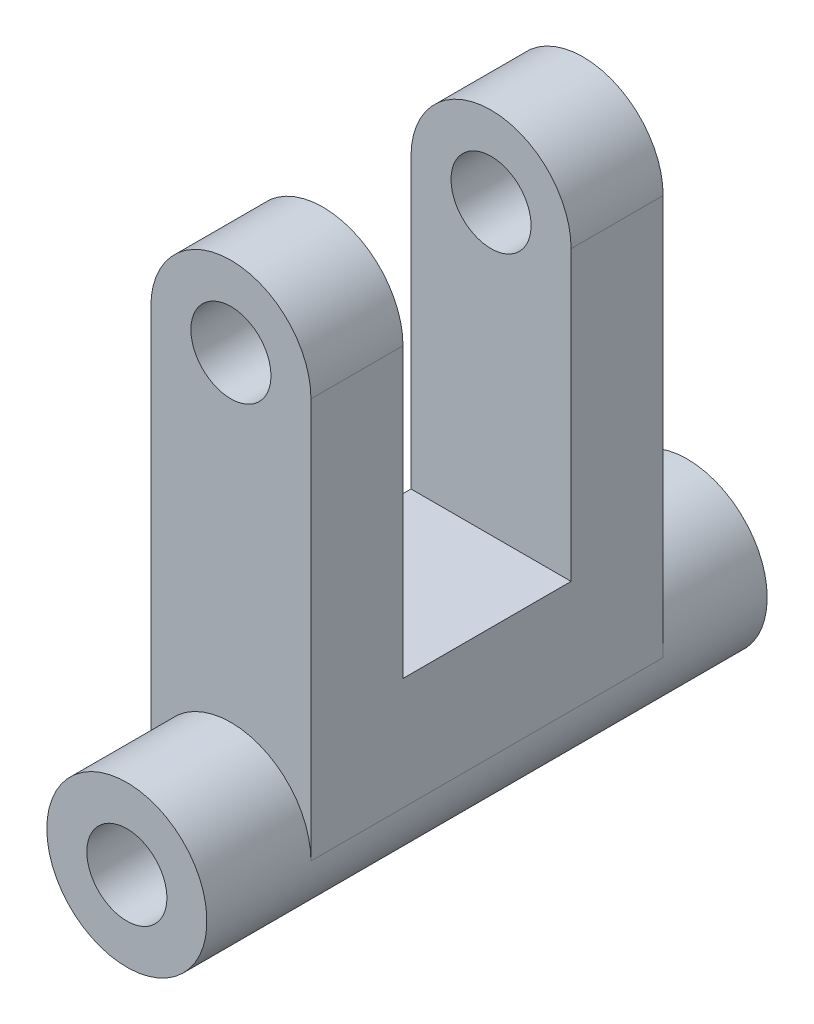
SolidWorks part; units mm, degrees
ref_plane "Front Plane" through (0, 0, 0) normal (0, 0, 1) x (1, 0, 0)
ref_plane "Top Plane" through (0, 0, 0) normal (0, 1, 0) x (1, 0, 0)
ref_plane "Right Plane" through (0, 0, 0) normal (1, 0, 0) x (0, 0, -1)
sketch "Sketch1" plane through (0, 0, 0) normal (0, 0, 1) x (1, 0, 0)
  line L0 (0, 0) -> (0, 25) construction
  line L1 (5, 25) -> (5, 0)
  line L2 (-5, 25) -> (-5, 0)
  circle A0 centre (0, 0) radius 5
  circle A1 centre (0, 0) radius 2.5
  circle A2 centre (0, 25) radius 5
  circle A3 centre (0, 25) radius 2.5
  dimension "D1" = 5
  dimension "D2" = 10
  dimension "D4" = 5
  dimension "D5" = 10
  dimension "D3" = 25
extrude "Boss-Extrude1" add sketch "Sketch1" along normal blind 5.75
sketch "Sketch2" plane through (0, 0, 5.75) normal (0, 0, 1) x (1, 0, 0)
  circle A0 centre (0, 25.0086) radius 2.5
  dimension "D1" = 5
extrude "Boss-Extrude2" add sketch "Sketch2" along normal blind 10.5 contours A0
sketch "Sketch3" plane through (0, 0, 5.75) normal (0, 0, 1) x (1, 0, 0)
  line L2 (5, 0) -> (5, 25)
  line L4 (-5, 0) -> (-5, 25)
  arc A0 (5, 25) -> (-5, 25) centre (0, 25) ccw
  arc A1 (-5, 0) -> (5, 0) centre (0, 0) ccw
extrude "Boss-Extrude3" add sketch "Sketch3" along normal blind 16.25
sketch "Sketch4" plane through (0, 0, 22) normal (0, 0, 1) x (1, 0, 0)
  circle A0 centre (0, 0) radius 5
  circle A1 centre (0, 0) radius 2.5
  dimension "D1" = 5
  dimension "D2" = 10
extrude "Boss-Extrude5" add sketch "Sketch4" along normal blind 8.5 contours A1 | A0
sketch "Sketch5" plane through (0, 0, 22) normal (0, 0, 1) x (1, 0, 0)
  circle A0 centre (0, 0) radius 2.5
extrude "Boss-Extrude6" add sketch "Sketch5" along normal blind 16.25
sketch "Sketch6" plane through (0, 0, 0) normal (0, 0, -1) x (-1, 0, 0)
  circle A0 centre (0, 0) radius 5
extrude "Boss-Extrude7" add sketch "Sketch6" along normal blind 8.5
sketch "Sketch7" plane through (0, 0, -8.5) normal (0, 0, -1) x (-1, 0, 0)
  circle A0 centre (0, 0) radius 2.5
  dimension "D1" = 5
extrude "Boss-Extrude8" add sketch "Sketch7" along normal blind 8
sketch "Sketch8" plane through (-5, 0, 0) normal (-1, 0, 0) x (0, 0, 1)
  line L1 (0, 30) -> (5.75, 30)
  line L2 (0, 30) -> (0, 7.7417)
  line L3 (0, 7.7417) -> (5.75, 7.7417)
  line L4 (5.75, 30) -> (5.75, 7.7417)
  line L5 (22, 30) -> (16.25, 30)
  line L6 (22, 30) -> (22, 7.7417)
  line L7 (22, 7.7417) -> (16.25, 7.7417)
  line L8 (16.25, 30) -> (16.25, 7.7417)
  line L9 (5.75, 30) -> (16.25, 30)
  line L10 (5.75, 30) -> (5.75, 7)
  line L11 (5.75, 7) -> (16.25, 7)
  line L12 (16.25, 30) -> (16.25, 7)
  line M10 (22, 25) -> (0, 25)
  dimension "D1" = 5.75
  dimension "D2" = 5.75
  dimension "D3" = 10.5
  dimension "D4" = 23
extrude "Cut-Extrude2" cut sketch "Sketch8" against normal blind 20 contours L12 L8 L4 L10 L11 M10 | L9 L4 L8 M10
sketch "Sketch9" plane through (0, 0, 22) normal (0, 0, 1) x (1, 0, 0)
  line L0 (0, -5) -> (0, 30) construction
  circle A0 centre (0, 0) radius 5 construction
  arc A1 (5, 25) -> (-5, 25) centre (0, 25) ccw construction
  circle A2 centre (0, 25) radius 5
  circle A3 centre (0, 25) radius 2.5
  dimension "D1" = 5
extrude "Boss-Extrude9" add sketch "Sketch9" against normal blind 22 contours A3
sketch "Sketch10" plane through (0, 0, -16.5) normal (0, 0, -1) x (-1, 0, 0)
  circle A0 centre (0, 0) radius 2.5
  dimension "D1" = 5
extrude "Cut-Extrude3" cut sketch "Sketch10" against normal blind 55
sketch "Sketch11" plane through (0, 0, 0) normal (0, 0, -1) x (-1, 0, 0)
  line L0 (5, 25) -> (-5, 25)
  circle A0 centre (0, 25) radius 2.5
  dimension "D1" = 5
extrude "Cut-Extrude4" cut sketch "Sketch11" against normal blind 22 contours L0 A0 | L0 A0
sketch "Sketch12" plane through (0, 0, 0) normal (1, 0, 0) x (0, 0, -1)
  line L0 (8.5, 0) -> (-30.5, 0)
  line L1 (8.5, -5) -> (8.5, 5) construction
  line L2 (-30.5, 5) -> (-30.5, -5) construction
  line L3 (8.5, 5) -> (0, 5) construction
  line L4 (8.5, -5) -> (7.5, -5)
  line L5 (8.5, -5) -> (8.5, 5)
  line L6 (8.5, 5) -> (7.5, 5)
  line L7 (7.5, -5) -> (7.5, 5)
  line L8 (-30.5, -5) -> (8.5, -5) construction
  line L9 (-30.5, 5) -> (-29.5, 5)
  line L10 (-30.5, 5) -> (-30.5, -5)
  line L11 (-30.5, -5) -> (-29.5, -5)
  line L12 (-29.5, 5) -> (-29.5, -5)
  dimension "D1" = 39
  dimension "D2" = 1
  dimension "D3" = 1
extrude "Cut-Extrude5" cut sketch "Sketch12" against normal mid plane 20 contours L7 L0 L5 L6 | L7 L4 L5 L0 | L12 L9 L10 L0 | L12 L0 L10 L11
sketch "Sketch13" plane through (5, 0, 0) normal (1, 0, 0) x (0, 0, -1)
  line L0 (-29.5, -5) -> (7.5, -5) construction
  line L1 (7.5, -5) -> (6.5, -5)
  line L2 (7.5, -5) -> (7.5, 5.6728)
  line L3 (7.5, 5.6728) -> (6.5, 5.6728)
  line L4 (6.5, -5) -> (6.5, 5.6728)
  line L5 (-29.5, 5) -> (-28.5, 5)
  line L6 (-29.5, 5) -> (-29.5, -5)
  line L7 (-29.5, -5) -> (-28.5, -5)
  line L8 (-28.5, 5) -> (-28.5, -5)
  dimension "D1" = 1
  dimension "D2" = 1
extrude "Cut-Extrude7" cut sketch "Sketch13" against normal blind 10
